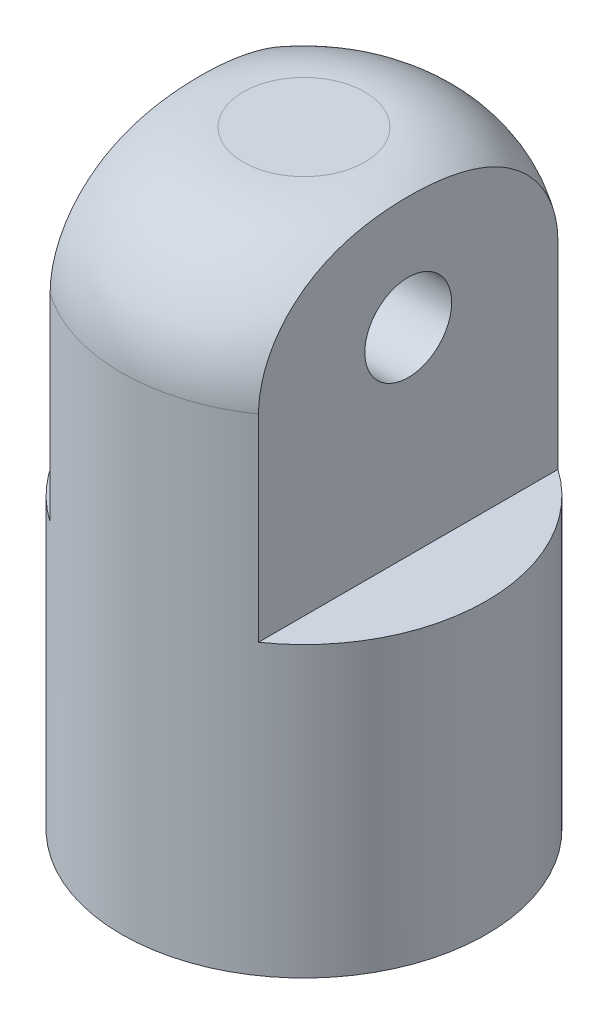
SolidWorks part; units mm, degrees
ref_plane "Спереди" through (0, 0, 0) normal (0, 0, 1) x (1, 0, 0)
ref_plane "Сверху" through (0, 0, 0) normal (0, 1, 0) x (1, 0, 0)
ref_plane "Справа" through (0, 0, 0) normal (1, 0, 0) x (0, 0, -1)
sketch "Эскиз1" plane through (0, 0, 0) normal (0, 1, 0) x (1, 0, 0)
  circle A0 centre (0, 0) radius 10.5
extrude "Вытянуть1" add sketch "Эскиз1" along normal blind 35
fillet "Скругление1" radius 7 1 edges at (0, 35, 10.5)
sketch "Эскиз2" plane through (0, 0, 0) normal (0, 0, 1) x (1, 0, 0)
  line L0 (0, 35) -> (0, 27.4885) construction
  line L1 (13.9586, 16.6235) -> (6, 16.6235)
  line L2 (-13.9586, 38.1666) -> (-6, 38.1666)
  line L3 (-13.9586, 38.1666) -> (-13.9586, 16.6235)
  line L4 (-13.9586, 16.6235) -> (-6, 16.6235)
  line L5 (-6, 38.1666) -> (-6, 16.6235)
  line L6 (6, 38.1666) -> (6, 16.6235)
  line L7 (13.9586, 38.1666) -> (6, 38.1666)
  line L8 (13.9586, 38.1666) -> (13.9586, 16.6235)
  dimension "D1" = 6
extrude "Вытянуть2" cut sketch "Эскиз2" against normal mid plane 40
sketch "Эскиз3" plane through (6, 0, 0) normal (1, 0, 0) x (0, 0, -1)
  circle A0 centre (0, 28.0115) radius 2.5
extrude "Вытянуть3" cut sketch "Эскиз3" against normal through all
